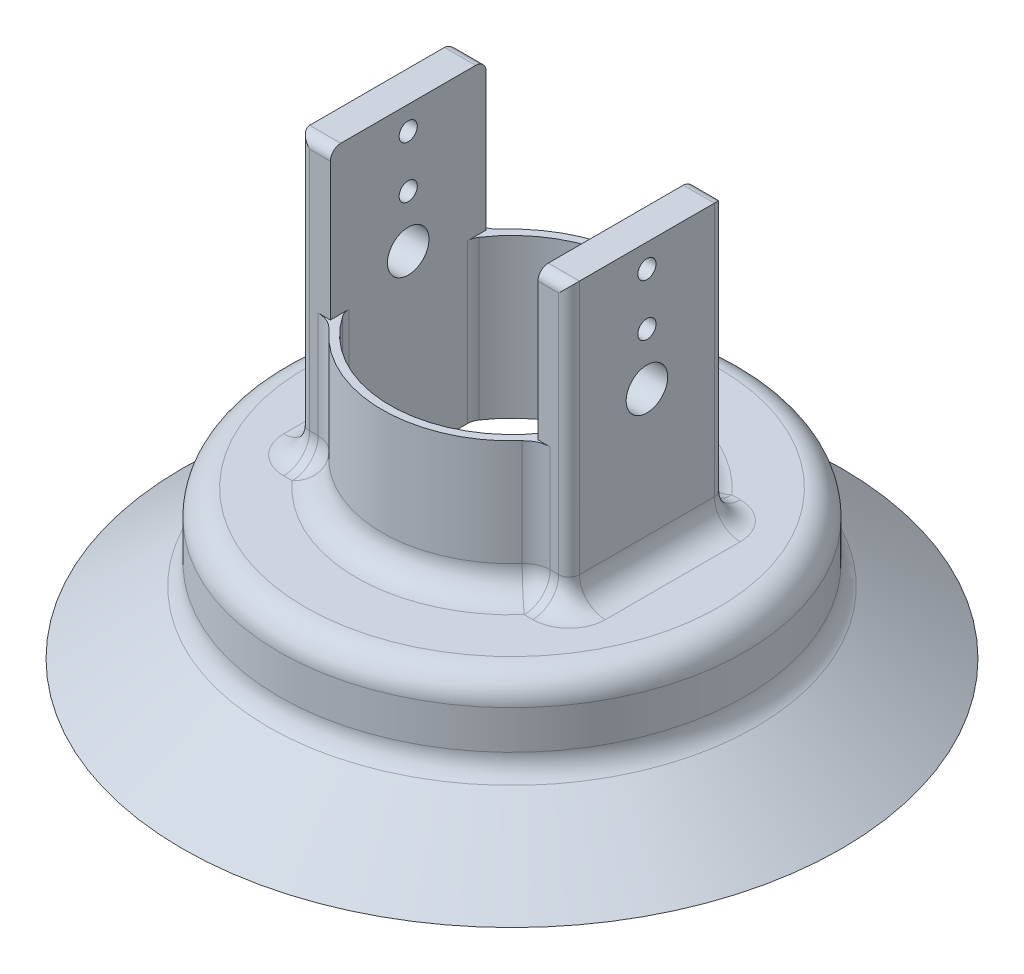
SolidWorks part; units mm, degrees
material "ABS"
ref_plane "前视基准面" through (0, 0, 0) normal (0, 0, 1) x (1, 0, 0)
ref_plane "上视基准面" through (0, 0, 0) normal (0, 1, 0) x (1, 0, 0)
ref_plane "右视基准面" through (0, 0, 0) normal (1, 0, 0) x (0, 0, -1)
other "Configuration Table"
sketch "草图1" plane through (0, 0, 0) normal (0, 1, 0) x (1, 0, 0)
  circle A0 centre (0, 0) radius 58.5
  circle A1 centre (0, 0) radius 63.5
  dimension "D1" = 117
  dimension "D2" = 127
ref_plane "基准面1" through (0, 13.5, 0) normal (0, 1, 0) x (1, 0, 0)
sketch "草图2" plane through (0, 13.5, 0) normal (0, 1, 0) x (1, 0, 0)
  circle A0 centre (0, 0) radius 39.75
  circle A1 centre (0, 0) radius 44.85
  dimension "D1" = 79.5
  dimension "D2" = 89.7
sketch "草图3" plane through (0, 0, 0) normal (1, 0, 0) x (0, 0, -1)
  line L0 (-44.85, 13.5) -> (-63.5, 0)
  line L1 (44.85, 13.5) -> (-44.85, 13.5) construction
  line L2 (63.5, 0) -> (-63.5, 0) construction
  line L3 (0, 0) -> (0, 13.5) construction
  line L4 (-44.85, 13.5) -> (0, 13.5) construction
  line L5 (-44.85, 13.5) -> (-39.75, 13.5)
  line L6 (-63.5, 0) -> (-58.5, 0)
  line L7 (-58.5, 0) -> (-39.75, 13.5)
  dimension "D1" = 13.5
  dimension "D2" = 89.7
  dimension "D3" = 127
  dimension "D4" = 79.5
  dimension "D5" = 117
revolve "旋转1" add sketch "草图3" angle 360 about L3
sketch "草图4" plane through (0, 13.5, 0) normal (0, 1, 0) x (1, 0, 0)
  circle A0 centre (0, 0) radius 39.75 construction
  circle A1 centre (0, 0) radius 44.85
  circle A2 centre (0, 0) radius 44.85
  circle A3 centre (0, 0) radius 39.75
  dimension "D1" = 0
extrude "凸台-拉伸1" add sketch "草图4" along normal blind 10
sketch "草图5" plane through (0, 23.5, 0) normal (0, 1, 0) x (1, 0, 0)
  line L0 (-20, 12.339) -> (-20, -12.339)
  line L1 (0, 0) -> (0, 23.5) construction
  line L2 (20, 12.339) -> (20, -12.339)
  circle A0 centre (0, 0) radius 44.85 construction
  circle A1 centre (0, 0) radius 44.85
  arc A2 (-20, -12.339) -> (20, -12.339) centre (0, 0) ccw
  arc A3 (20, 12.339) -> (-20, 12.339) centre (0, 0) ccw
  dimension "D1" = 47
  dimension "D2" = 40
extrude "凸台-拉伸2" add sketch "草图5" along normal blind 5
sketch "草图6" plane through (0, 28.5, 0) normal (0, 1, 0) x (1, 0, 0)
  line L2 (20, -12.339) -> (20, 12.339) construction
  line L3 (-20, 12.339) -> (-20, -12.339) construction
  line L4 (20, -12.339) -> (20, 12.339)
  line L5 (-20, 12.339) -> (-20, -12.339)
  line L6 (0, 0) -> (-23, 0) construction
  line L7 (0, 0) -> (0, 23.5) construction
  line L8 (-26, -15) -> (-20, -15)
  line L9 (-26, -15) -> (-26, 15)
  line L10 (-26, 15) -> (-20, 15)
  line L12 (-26, -15) -> (-20, 15) construction
  line L13 (-26, 15) -> (-20, -15) construction
  line L14 (26, 15) -> (20, 15)
  line L16 (26, -15) -> (20, -15)
  line L17 (26, -15) -> (26, 15)
  line L19 (-20, -12.339) -> (-20, 12.339)
  line L20 (20, -12.339) -> (20, 12.339)
  circle A0 centre (0, 0) radius 25 construction
  arc A2 (-20, 15) -> (20, 15) centre (0, 0) cw
  arc A3 (-20, -12.339) -> (20, -12.339) centre (0, 0) ccw construction
  arc A4 (20, 12.339) -> (-20, 12.339) centre (0, 0) ccw construction
  arc A5 (-20, -12.339) -> (20, -12.339) centre (0, 0) ccw
  arc A6 (20, 12.339) -> (-20, 12.339) centre (0, 0) ccw
  arc A7 (20, -15) -> (-20, -15) centre (0, 0) cw
  dimension "D1" = 50
  dimension "D3" = 6
extrude "凸台-拉伸3" add sketch "草图6" along normal blind 25.5
sketch "草图7" plane through (0, 54, 0) normal (0, 1, 0) x (1, 0, 0)
  line L5 (-26, 15) -> (-20, 15)
  line L6 (-26, 15) -> (-26, -15)
  line L7 (-26, -15) -> (-20, -15)
  line L8 (-20, 15) -> (-20, -15)
  line L9 (26, -15) -> (20, -15)
  line L10 (26, -15) -> (26, 15)
  line L11 (26, 15) -> (20, 15)
  line L12 (20, -15) -> (20, 15)
extrude "凸台-拉伸4" add sketch "草图7" along normal blind 28.5
sketch "草图8" plane through (-26, 0, 0) normal (-1, 0, 0) x (0, 0, 1)
  line L0 (0, 82.5) -> (0, 28.5) construction
  line L1 (-15, 82.5) -> (15, 82.5) construction
  line L2 (44.85, 28.5) -> (-44.85, 28.5) construction
  circle A0 centre (0, 78) radius 1.75
  circle A1 centre (0, 68) radius 1.75
  circle A2 centre (0, 58) radius 4
  dimension "D1" = 4.5
  dimension "D2" = 10
  dimension "D3" = 3.5
  dimension "D4" = 8
  dimension "D5" = 10
extrude "切除-拉伸1" cut sketch "草图8" against normal through all
fillet "圆角1" radius 5 4 edges at (20, 41.25, 15) (-20, 41.25, 15) (20, 41.25, -15) (-20, 41.25, -15)
fillet "圆角2" radius 2 8 edges at (-26, 55.5, -15) (26, 55.5, -15) (-26, 55.5, 15) (26, 55.5, 15) (-23, 82.5, 15) (-23, 82.5, -15) (23, 82.5, 15) (23, 82.5, -15)
fillet "圆角3" radius 5 18 edges at (-20.3194, 28.5, -15.4356) (-23.1803, 28.5, -15) (-25.4142, 28.5, -14.4142) (-26, 28.5, 0) (-25.4142, 28.5, 14.4142) (-23.1803, 28.5, 15) (-20.3194, 28.5, 15.4356) (0, 28.5, 25) (20.3194, 28.5, 15.4356) (23.1803, 28.5, 15) (25.4142, 28.5, 14.4142) (26, 28.5, 0) (25.4142, 28.5, -14.4142) (23.1803, 28.5, -15) (20.3194, 28.5, -15.4356) (0, 28.5, -25) (0, 13.5, 44.85) (0, 28.5, 44.85)
fillet "圆角4" radius 3 6 edges at (0, 13.5, -39.75) (-20, 38.75, 12.339) (-20, 38.75, -12.339) (20, 38.75, 12.339) (20, 38.75, -12.339) (0, 23.5, 39.75)
fillet "圆角5" radius 3 1 edges at (0, 0, -58.5)
